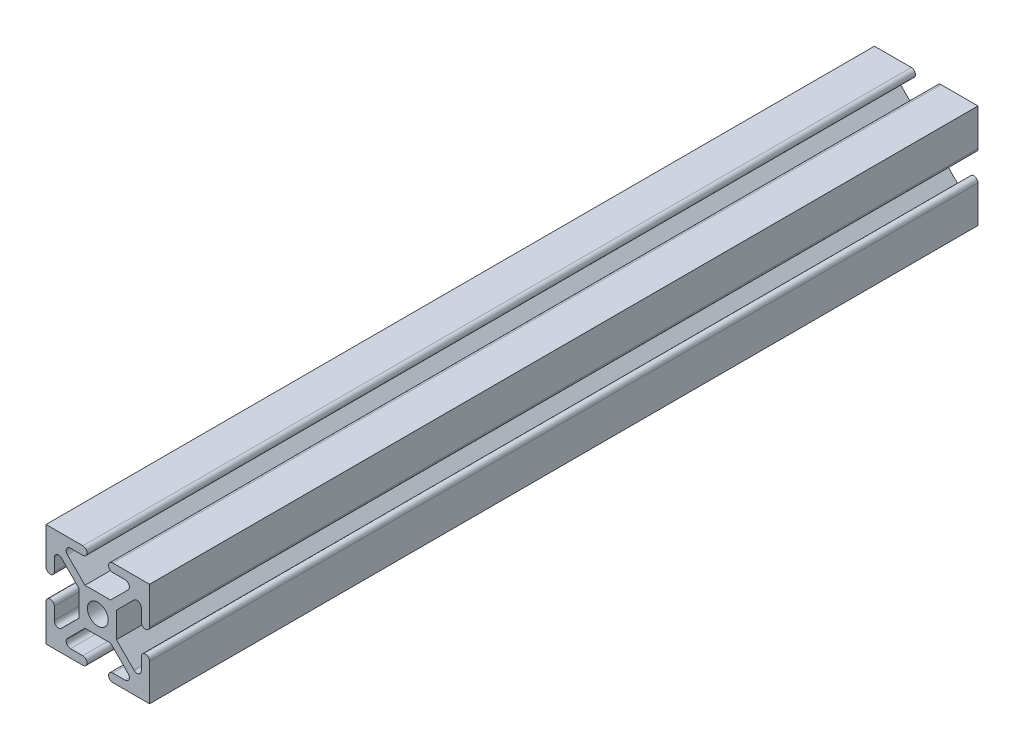
SolidWorks part; units mm, degrees
ref_plane "Front Plane" through (0, 0, 0) normal (0, 0, 1) x (1, 0, 0)
ref_plane "Top Plane" through (0, 0, 0) normal (0, 1, 0) x (1, 0, 0)
ref_plane "Right Plane" through (0, 0, 0) normal (1, 0, 0) x (0, 0, -1)
sketch "Sketch2" plane through (0, 0, 0) normal (0, 0, 1) x (1, 0, 0)
  line L0 (9.4142, 17) -> (5.1716, 21.2426)
  line L5 (9.4142, 17) -> (12.5, 17)
  line L9 (5.8995, 23) -> (8.8995, 23)
  line L10 (8.8995, 25) -> (0, 25)
  line L11 (0, 25) -> (8.8995, 25)
  line L12 (0, 16.1005) -> (0, 25)
  line L13 (2, 19.1005) -> (2, 16.1005)
  line L14 (8, 15.5858) -> (3.7574, 19.8284)
  line L15 (0, 25) -> (35355.3391, -35330.3391) construction
  line L16 (12.5, 12.5) -> (35367.8391, 35367.8391) construction
  line L17 (12.6363, 12.5) -> (50012.6363, 12.5) construction
  line L18 (12.5, 12.3637) -> (12.5, 50012.3637) construction
  line L19 (8, 15.5858) -> (8, 12.5)
  line L20 (9.4142, 8) -> (12.5, 8)
  line L21 (9.4142, 8) -> (5.1716, 3.7574)
  line L22 (5.8995, 2) -> (8.8995, 2)
  line L23 (8.8995, 0) -> (0, 0)
  line L24 (0, 8.8995) -> (0, 0)
  line L25 (2, 5.8995) -> (2, 8.8995)
  line L26 (8, 9.4142) -> (8, 12.5)
  line L27 (8, 9.4142) -> (3.7574, 5.1716)
  line L28 (15.5858, 17) -> (12.5, 17)
  line L29 (15.5858, 17) -> (19.8284, 21.2426)
  line L30 (19.1005, 23) -> (16.1005, 23)
  line L31 (16.1005, 25) -> (25, 25)
  line L32 (25, 16.1005) -> (25, 25)
  line L33 (23, 19.1005) -> (23, 16.1005)
  line L34 (17, 15.5858) -> (21.2426, 19.8284)
  line L35 (17, 15.5858) -> (17, 12.5)
  line L36 (17, 9.4142) -> (17, 12.5)
  line L37 (15.5858, 8) -> (12.5, 8)
  line L38 (17, 9.4142) -> (21.2426, 5.1716)
  line L39 (23, 5.8995) -> (23, 8.8995)
  line L40 (25, 8.8995) -> (25, 0)
  line L41 (16.1005, 0) -> (25, 0)
  line L42 (19.1005, 2) -> (16.1005, 2)
  line L43 (15.5858, 8) -> (19.8284, 3.7574)
  arc A0 (5.1716, 21.2426) -> (5.8995, 23) centre (5.8995, 21.9706) cw
  arc A1 (0, 16.1005) -> (2, 16.1005) centre (1, 16.1005) ccw
  arc A2 (8.8995, 25) -> (8.8995, 23) centre (8.8995, 24) cw
  arc A3 (3.7574, 19.8284) -> (2, 19.1005) centre (3.0294, 19.1005) ccw
  arc A4 (5.1716, 3.7574) -> (5.8995, 2) centre (5.8995, 3.0294) ccw
  arc A5 (8.8995, 0) -> (8.8995, 2) centre (8.8995, 1) ccw
  arc A6 (0, 8.8995) -> (2, 8.8995) centre (1, 8.8995) cw
  arc A7 (3.7574, 5.1716) -> (2, 5.8995) centre (3.0294, 5.8995) cw
  arc A8 (19.8284, 21.2426) -> (19.1005, 23) centre (19.1005, 21.9706) ccw
  arc A9 (16.1005, 25) -> (16.1005, 23) centre (16.1005, 24) ccw
  arc A10 (25, 16.1005) -> (23, 16.1005) centre (24, 16.1005) cw
  arc A11 (21.2426, 19.8284) -> (23, 19.1005) centre (21.9706, 19.1005) cw
  arc A12 (19.8284, 3.7574) -> (19.1005, 2) centre (19.1005, 3.0294) cw
  arc A13 (21.2426, 5.1716) -> (23, 5.8995) centre (21.9706, 5.8995) ccw
  arc A14 (25, 8.8995) -> (23, 8.8995) centre (24, 8.8995) ccw
  arc A15 (16.1005, 0) -> (16.1005, 2) centre (16.1005, 1) cw
  circle A16 centre (12.5, 12.5) radius 2.5
  dimension "D14" = 5
  dimension "D2" = 1.0294
  dimension "D3" = 12.5
  dimension "D4" = 12.5
  dimension "D5" = 17.6777
  dimension "D7" = 45
  dimension "D9" = 12.5
  dimension "D10" = 6
  dimension "D11" = 3
  dimension "D12" = 1
  dimension "D13" = 2
extrude "Boss-Extrude1" add sketch "Sketch2" along normal blind 200 contours A15 L41 L40 A14 L39 A13 L38 L36 L35 L34 A11 L33 A10 L32 L31 A9 L30 A8 L29 L28 L5 L0 A0 L9 A2 L10 L12 A1 L13 A3 L14 L19 L26 L27 A7 L25 A6 L24 L23 A5 L22 A4 L21 L20 L37 L43 A12 L42 A16
